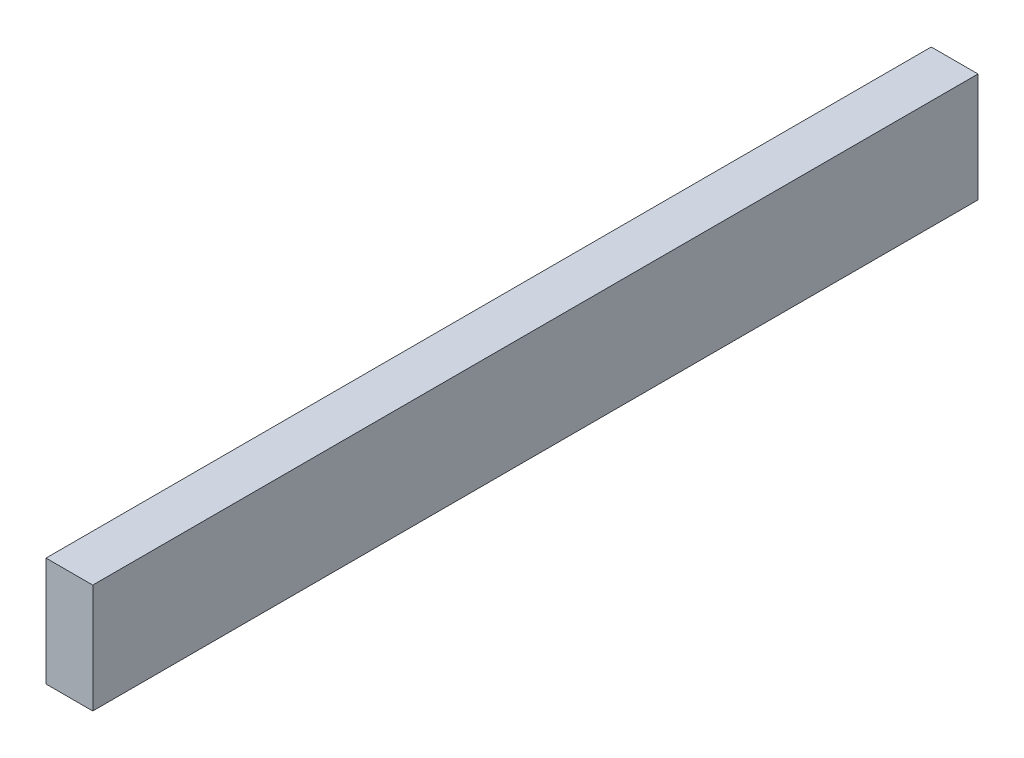
SolidWorks part; units mm, degrees
material "SPF Select 2Btr Grade Lumber"
ref_plane "Front Plane" through (0, 0, 0) normal (0, 0, 1) x (1, 0, 0)
ref_plane "Top Plane" through (0, 0, 0) normal (0, 1, 0) x (1, 0, 0)
ref_plane "Right Plane" through (0, 0, 0) normal (1, 0, 0) x (0, 0, -1)
sketch "Sketch2" plane through (0, 0, 0) normal (0, 0, 1) x (1, 0, 0)
  line L1 (0, 0) -> (38.1, 0)
  line L2 (0, 0) -> (0, 88.9)
  line L3 (0, 88.9) -> (38.1, 88.9)
  line L4 (38.1, 0) -> (38.1, 88.9)
  dimension "D1" = 38.1
  dimension "D2" = 88.9
extrude "Boss-Extrude1" add sketch "Sketch2" along normal blind 721.45
